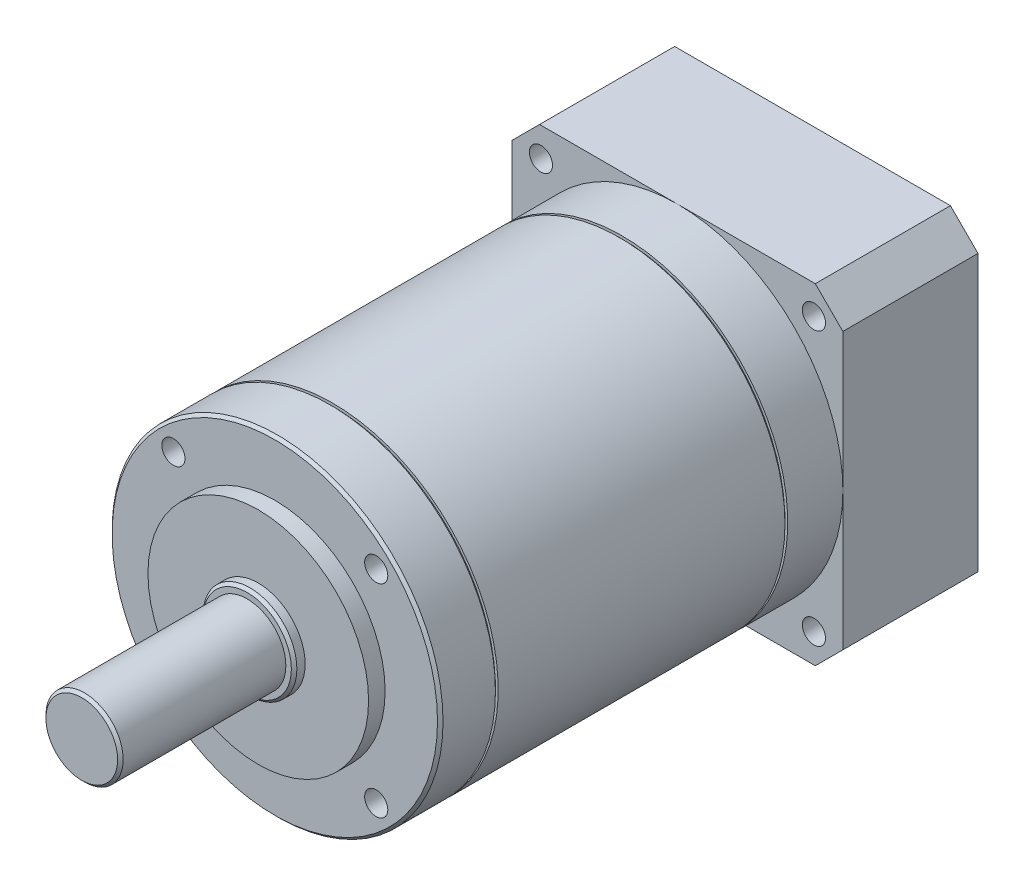
SolidWorks part; units mm, degrees
ref_plane "前视基准面" through (0, 0, 0) normal (0, 0, 1) x (1, 0, 0)
ref_plane "上视基准面" through (0, 0, 0) normal (0, 1, 0) x (1, 0, 0)
ref_plane "右视基准面" through (0, 0, 0) normal (1, 0, 0) x (0, 0, -1)
sketch "草图1" plane through (0, 0, 0) normal (0, 0, 1) x (1, 0, 0)
  line L1 (-30, -30) -> (30, -30)
  line L2 (-30, -30) -> (-30, 30)
  line L3 (-30, 30) -> (30, 30)
  line L4 (30, -30) -> (30, 30)
  line L5 (-30, -30) -> (30, 30) construction
  line L6 (-30, 30) -> (30, -30) construction
  point P0 (0, 0)
  dimension "D1" = 60
  dimension "D2" = 60
extrude "凸台-拉伸1" add sketch "草图1" along normal blind 24.5
ref_plane "基准面1" through (0, 0, 0) normal (1, 0, 0) x (0, 0, -1)
ref_plane "基准面2" through (0, 0, 0) normal (0, 1, 0) x (1, 0, 0)
chamfer "倒角1" distance 5 angle 45 4 edges at (-30, -30, 12.25) (30, -30, 12.25) (30, 30, 12.25) (-30, 30, 12.25)
sketch "草图2" plane through (0, 0, 24.5) normal (0, 0, 1) x (1, 0, 0)
  circle A0 centre (0, 0) radius 30
  dimension "D1" = 60
extrude "凸台-拉伸2" add sketch "草图2" along normal blind 73
sketch "草图3" plane through (0, 0, 0) normal (1, 0, 0) x (0, 0, -1)
  line L0 (0, 0) -> (-124.5733, 0) construction
  line L1 (13.475, 0) -> (-13.475, 0) construction
  line L2 (-97.5, 30) -> (-97.5, -30) construction
  line L3 (-87.5, 33.2688) -> (-87, 33.2688)
  line L4 (-87.5, 33.2688) -> (-87.5, 29.5)
  line L5 (-87.5, 29.5) -> (-87, 29.5)
  line L6 (-87, 33.2688) -> (-87, 29.5)
  line L7 (-35, 33.2688) -> (-34.5, 33.2688)
  line L8 (-35, 33.2688) -> (-35, 29.5)
  line L9 (-35, 29.5) -> (-34.5, 29.5)
  line L10 (-34.5, 33.2688) -> (-34.5, 29.5)
  line L11 (-24.5, 30) -> (-24.5, 0) construction
  line L12 (-24.5, 30) -> (-97.5, 30) construction
  dimension "D1" = 0.5
  dimension "D2" = 0.5
  dimension "D3" = 10
  dimension "D4" = 10
  dimension "D5" = 0.5
revolve "切除-旋转1" cut sketch "草图3" angle 360 about L0
sketch "草图4" plane through (0, 0, 97.5) normal (0, 0, 1) x (1, 0, 0)
  circle A0 centre (0, 0) radius 7
  dimension "D1" = 14
extrude "凸台-拉伸3" add sketch "草图4" along normal blind 35
sketch "草图5" plane through (0, 0, 97.5) normal (0, 0, 1) x (1, 0, 0)
  circle A0 centre (0, 0) radius 20
  dimension "D1" = 40
extrude "凸台-拉伸4" add sketch "草图5" along normal blind 3
sketch "草图6" plane through (0, 0, 100.5) normal (0, 0, 1) x (1, 0, 0)
  circle A0 centre (0, 0) radius 8.5
  dimension "D1" = 17
extrude "凸台-拉伸5" add sketch "草图6" along normal blind 2
hole_wizard "M5 螺纹孔1" positions "草图8" profile "草图7" tap size "M5" standard "GB"
sketch "草图8" plane through (0, 0, 97.5) normal (0, 0, 1) x (1, 0, 0)
  line L0 (0, 0) -> (27.5, 27.5) construction
  line L1 (30, 25) -> (25, 30) construction
  point P0 (18.3848, 18.3848)
  dimension "D1" = 26
sketch "草图7" plane through (18.3848, 18.3848, 97.5) normal (1, 0, 0) x (0, -1, 0)
  line L0 (0, 0) -> (0, 13.6618)
  line L1 (0, 13.6618) -> (2.1, 12.4)
  line L2 (2.1, 12.4) -> (2.1, 0)
  line L5 (2.1, 0) -> (0, 0)
  line L10 (0, 13.6618) -> (-2.1, 12.4) construction
  line L11 (0, -6.35) -> (0, 107.95) construction
  dimension "螺纹孔钻头直径" = 4.2
  dimension "螺纹孔钻头深度" = 12.4
  dimension "导头角度" = 118
cosmetic thread "孔螺蚊线1" parameters "D1"=12.4, "D2"=5
pattern_circular "阵列(圆周)1" count 4 every 90 about axis through (0, 0, 0) along (0, 0, 1) of "M5 螺纹孔1"
hole_wizard "M5 螺纹孔2" positions "草图10" profile "草图9" tap size "M5" standard "GB" end condition through all
sketch "草图10" plane through (0, 0, 0) normal (0, 0, -1) x (-1, 0, 0)
  line L0 (0, 0) -> (27.5, 27.5) construction
  line L1 (30, 25) -> (25, 30) construction
  point P0 (24.7487, 24.7487)
  dimension "D1" = 35
sketch "草图9" plane through (-24.7487, 24.7487, 0) normal (1, 0, 0) x (0, 1, 0)
  line L0 (0, 0) -> (0, 132.5)
  line L1 (0, 132.5) -> (2.1, 132.5)
  line L2 (2.1, 132.5) -> (2.1, 0)
  line L5 (2.1, 0) -> (0, 0)
  line L11 (0, -6.35) -> (0, 107.95) construction
  dimension "通孔螺纹孔钻头直径" = 4.2
  dimension "通孔螺纹孔钻头深度" = 132.5
cosmetic thread "孔螺蚊线2" parameters "D2"=5
pattern_circular "阵列(圆周)2" count 4 every 90 about axis through (0, 0, 0) along (0, 0, 1) of "M5 螺纹孔2"
chamfer "倒角2" distance 0.5 angle 45 3 edges at (30, 0, 97.5) (7, 0, 132.5) (8.5, 0, 102.5)
